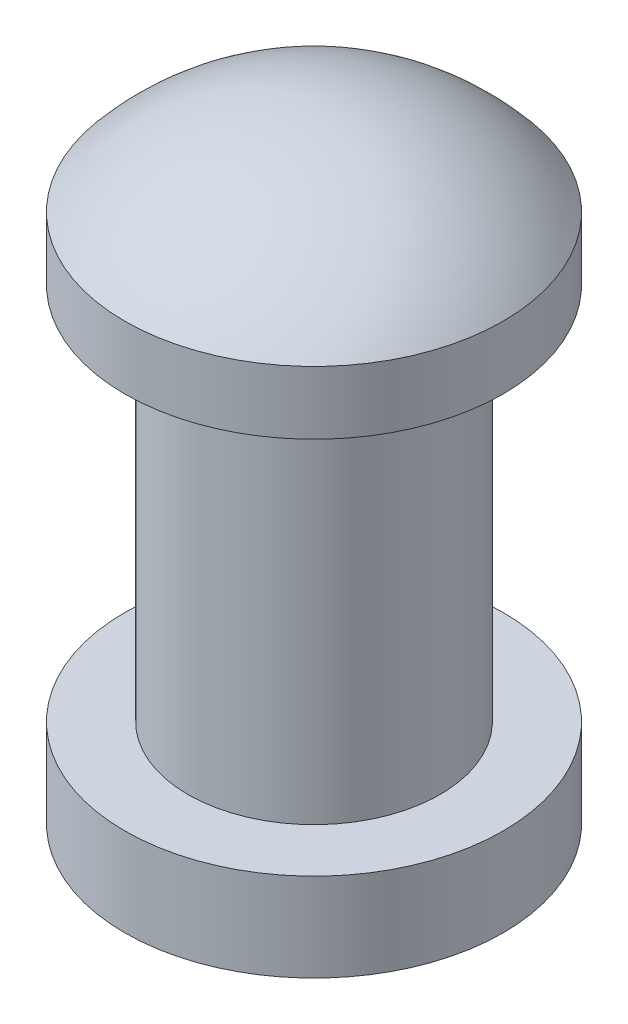
SolidWorks part; units mm, degrees
material "1060 Alloy"
ref_plane "Front Plane" through (0, 0, 0) normal (0, 0, 1) x (1, 0, 0)
ref_plane "Top Plane" through (0, 0, 0) normal (0, 1, 0) x (1, 0, 0)
ref_plane "Right Plane" through (0, 0, 0) normal (1, 0, 0) x (0, 0, -1)
sketch "Sketch1" plane through (0, 0, 0) normal (0, 0, 1) x (1, 0, 0)
  line L0 (0, 2) -> (0, -2) construction
  line L1 (0.75, 1.65) -> (0.75, 1.4)
  line L2 (0.75, 1.4) -> (0.5, 1.4)
  line L3 (0.5, 1.4) -> (0.5, -0.1)
  line L4 (0.5, -0.1) -> (0.75, -0.1)
  line L5 (0.75, -0.1) -> (0.75, -0.45)
  line L6 (0.75, -0.45) -> (0, -0.45)
  line L7 (0, 2) -> (0, -0.45)
  arc A0 (0, 2) -> (0.75, 1.65) centre (0, 1.0214) cw
  dimension "D8" = 4
  dimension "D1" = 0.25
  dimension "D2" = 0.35
  dimension "D3" = 0.75
  dimension "D4" = 1
  dimension "D5" = 0.35
  dimension "D6" = 1.5
  dimension "D7" = 0.75
revolve "Revolve1" add sketch "Sketch1" angle 360 about L0
